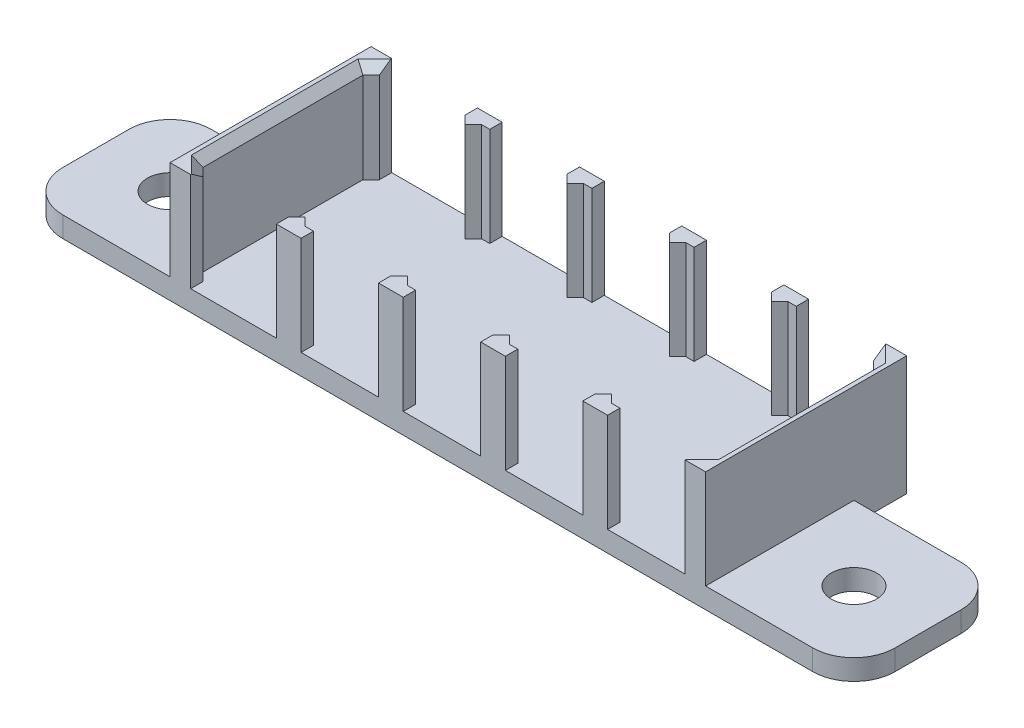
SolidWorks part; units mm, degrees
ref_plane "Спереди" through (0, 0, 0) normal (0, 0, 1) x (1, 0, 0)
ref_plane "Сверху" through (0, 0, 0) normal (0, 1, 0) x (1, 0, 0)
ref_plane "Справа" through (0, 0, 0) normal (1, 0, 0) x (0, 0, -1)
sketch "Эскиз1" plane through (0, 0, 0) normal (0, 1, 0) x (1, 0, 0)
  line L0 (0, 0) -> (0, 14.4286) construction
  line L1 (32.5, 14.4286) -> (32.5, -9.9714)
  line L2 (32.5, 14.4286) -> (-32.5, 14.4286)
  line L4 (32.5, -9.9714) -> (-32.5, -9.9714)
  line L5 (-32.5, 14.4286) -> (-32.5, -9.9714)
  point P7 (0, -9.9714)
  dimension "D1" = 32.5
  dimension "D2" = 24.4
extrude "Бобышка-Вытянуть1" add sketch "Эскиз1" along normal blind 2.5
sketch "Эскиз2" plane through (0, 0, 0) normal (0, 1, 0) x (1, 0, 0)
  line L0 (-32.5, 8.0286) -> (-50.5, -9.9714) construction
  line L1 (-32.5, -9.9714) -> (-45.5, -9.9714)
  line L2 (-32.5, -9.9714) -> (-32.5, 8.0286)
  line L3 (-32.5, 8.0286) -> (-45.5, 8.0286)
  line L4 (-50.5, -4.9714) -> (-50.5, 3.0286)
  arc A0 (-45.5, -9.9714) -> (-50.5, -4.9714) centre (-45.5, -4.9714) cw
  arc A1 (-50.5, 3.0286) -> (-45.5, 8.0286) centre (-45.5, 3.0286) cw
  circle A3 centre (-41.5, -0.9714) radius 2.75
  point P7 (-50.5, -9.9714)
  point P10 (-50.5, 8.0286)
  dimension "D3" = 5
  dimension "D4" = 5.5
  dimension "D1" = 18
  dimension "D2" = 18
extrude "Бобышка-Вытянуть2" add sketch "Эскиз2" along normal blind 2.5 contours A1 L3 L2 L1 A0 L4
mirror "Зеркальное отражение1" about plane through (0, 0, 0) normal (1, 0, 0) of "Бобышка-Вытянуть2"
sketch "Эскиз3" plane through (0, 2.5, 0) normal (0, 1, 0) x (1, 0, 0)
  line L1 (-32.5, 14.4286) -> (-31, 14.4286)
  line L2 (-32.5, 14.4286) -> (-32.5, -9.9714)
  line L5 (-31, 14.4286) -> (-30, 14.4286)
  line L6 (32.5, 14.4286) -> (-32.5, 14.4286) construction
  line L7 (-30, 14.4286) -> (-30, 12.9286)
  line L8 (-30, 12.9286) -> (-31, 11.9286)
  line L9 (-31, 14.4286) -> (-31, 13.0893) construction
  line L13 (-31, 2.2286) -> (-32.5, 2.2286) construction
  line L14 (-32.5, -9.9714) -> (-31, -9.9714)
  line L15 (-31, -9.9714) -> (-30, -9.9714)
  line L16 (-30, -8.4714) -> (-31, -7.4714)
  line L17 (-30, -9.9714) -> (-30, -8.4714)
  line L18 (-31, 11.9286) -> (-31, -7.4714)
  dimension "D1" = 1.5
  dimension "D2" = 1.5
  dimension "D3" = 1
  dimension "D4" = 135
  dimension "D5" = 24.4
extrude "Бобышка-Вытянуть3" add sketch "Эскиз3" along normal blind 12
mirror "Зеркальное отражение2" about plane through (0, 0, 0) normal (1, 0, 0) of "Бобышка-Вытянуть3"
chamfer "Фаска1" distance 1 angle 45 6 edges at (-30.5, 14.5, -12.4286) (30.5, 14.5, -12.4286) (-30.5, 14.5, 7.9714) (-31, 14.5, -2.2286) (30.5, 14.5, 7.9714) (31, 14.5, -2.2286)
sketch "Эскиз4" plane through (0, 2.5, 0) normal (0, 1, 0) x (1, 0, 0)
  line L0 (-31, -17.4714) -> (-31, -9.9714) construction
  line L2 (-31, -9.9714) -> (-18.6, -9.9714) construction
  line L4 (-18.6, -9.9714) -> (-19.6, -9.9714)
  line L5 (-19.6, -9.9714) -> (-19.6, -8.4714)
  line L6 (-19.6, -8.4714) -> (-18.6, -8.4714) construction
  line L7 (-18.6, -8.4714) -> (-18.6, -7.4714) construction
  line L8 (-19.6, -8.4714) -> (-18.6, -7.4714)
  line L9 (-18.6, -8.4714) -> (-17.6, -8.4714) construction
  line L10 (-18.6, -7.4714) -> (-17.6, -8.4714)
  line L11 (-17.6, -8.4714) -> (-16.6, -8.4714)
  line L12 (-16.6, -8.4714) -> (-16.6, -9.9714)
  line L13 (-16.6, -9.9714) -> (-18.6, -9.9714)
  line L14 (-45.5, -9.9714) -> (-32.5, -9.9714) construction
  line L16 (-31, -7.4714) -> (-31, 11.9286) construction
  dimension "D1" = 12.4
  dimension "D2" = 1
  dimension "D3" = 1.5
  dimension "D4" = 1
  dimension "D5" = 1
  dimension "D6" = 1
  dimension "D7" = 1
extrude "Бобышка-Вытянуть4" add sketch "Эскиз4" along normal blind 12
ref_plane "Плоскость1" through (0, 0, -2.2286) normal (0, 0, 1) x (1, 0, 0)
mirror "Зеркальное отражение3" about plane through (0, 0, -2.2286) normal (0, 0, 1) of "Бобышка-Вытянуть4"
pattern_linear "Линейный массив1" count 4 spacing 12.4 along (1, 0, 0) of "Зеркальное отражение3", "Бобышка-Вытянуть4"
